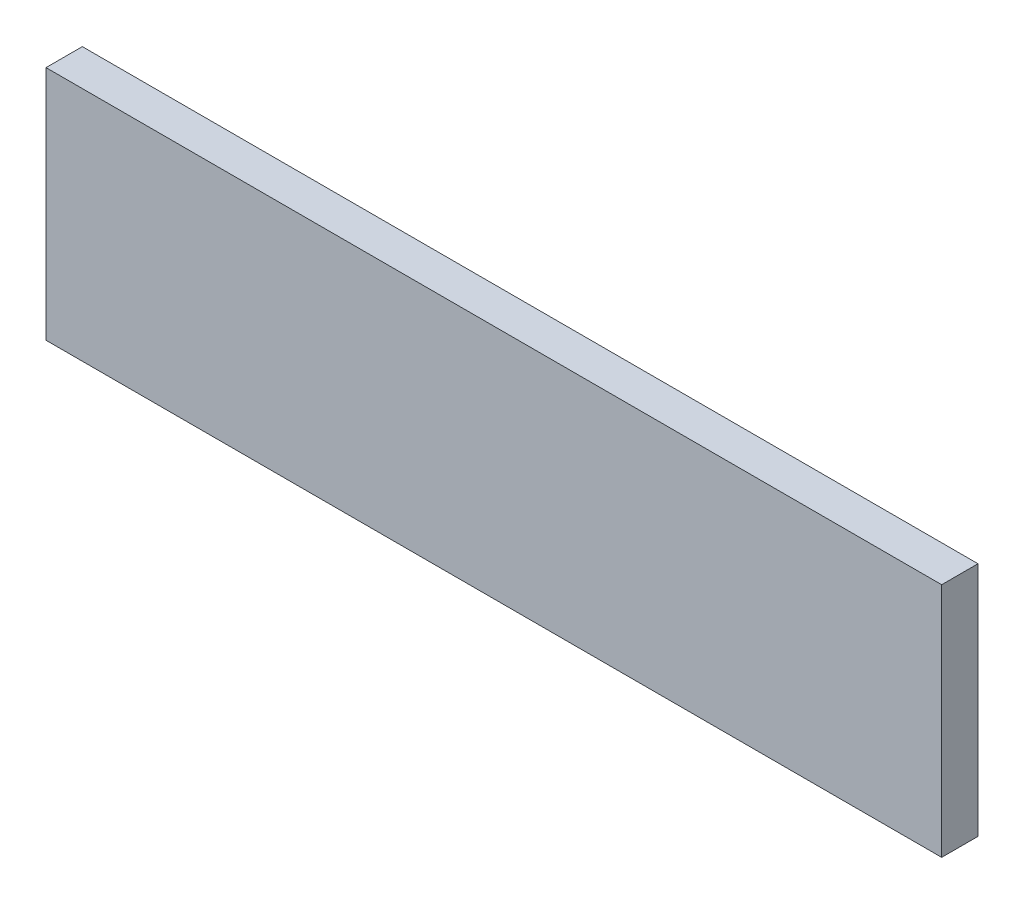
SolidWorks part; units mm, degrees
ref_plane "Plan de face" through (0, 0, 0) normal (0, 0, 1) x (1, 0, 0)
ref_plane "Plan de dessus" through (0, 0, 0) normal (0, 1, 0) x (1, 0, 0)
ref_plane "Plan de droite" through (0, 0, 0) normal (1, 0, 0) x (0, 0, -1)
sketch "Esquisse1" plane through (0, 0, 0) normal (0, 0, 1) x (1, 0, 0)
  line L1 (-156.55, 41.275) -> (156.55, 41.275)
  line L2 (-156.55, 41.275) -> (-156.55, -41.275)
  line L3 (-156.55, -41.275) -> (156.55, -41.275)
  line L4 (156.55, 41.275) -> (156.55, -41.275)
  line L5 (-156.55, 41.275) -> (156.55, -41.275) construction
  line L6 (-156.55, -41.275) -> (156.55, 41.275) construction
  point P0 (0, 0)
  dimension "D1" = 313.1
  dimension "D2" = 82.55
extrude "Boss.-Extru.1" add sketch "Esquisse1" along normal blind 12.7
